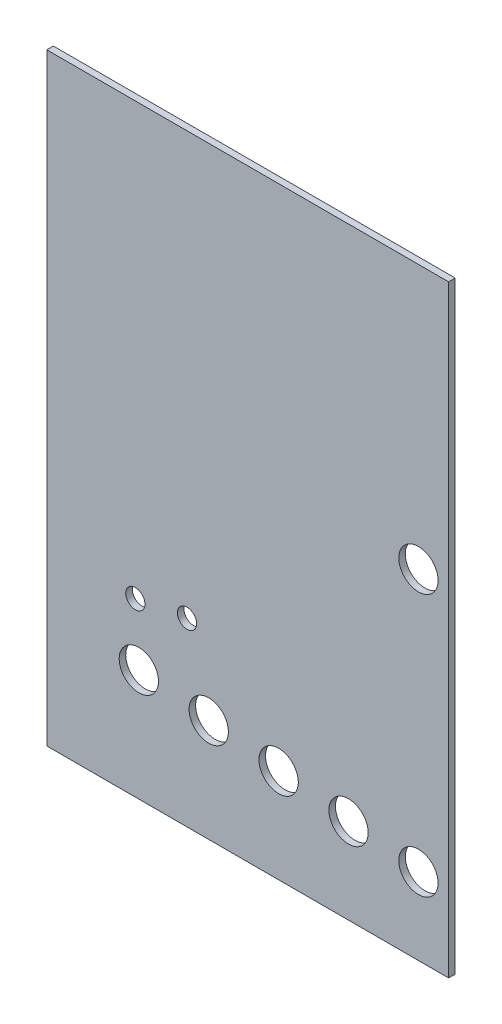
SolidWorks part; units mm, degrees
material "Polypropylene"
ref_plane "Front Plane" through (0, 0, 0) normal (0, 0, 1) x (1, 0, 0)
ref_plane "Top Plane" through (0, 0, 0) normal (0, 1, 0) x (1, 0, 0)
ref_plane "Right Plane" through (0, 0, 0) normal (1, 0, 0) x (0, 0, -1)
sketch "Sketch1" plane through (0, 0, 0) normal (0, 0, 1) x (1, 0, 0)
  line L0 (64.3744, -313.2564) -> (64.3744, -356.9444) construction
  line L1 (0, 0) -> (292.1, 0)
  line L2 (0, 0) -> (0, -438.15)
  line L3 (0, -438.15) -> (292.1, -438.15)
  line L4 (292.1, 0) -> (292.1, -438.15)
  line L5 (64.3744, -313.2564) -> (101.9257, -306.8134) construction
  line L6 (64.3744, -313.2564) -> (101.9257, -313.2564) construction
  line L7 (101.9257, -313.2564) -> (101.9257, -306.8134) construction
  line L8 (64.3744, -356.9444) -> (66.9144, -356.9444) construction
  line L9 (66.9144, -356.9444) -> (117.7144, -356.9444) construction
  line L10 (117.7144, -356.9444) -> (117.7144, -363.2944) construction
  line L11 (117.7144, -363.2944) -> (168.5144, -363.2944) construction
  line L12 (168.5144, -363.2944) -> (168.5144, -369.6444) construction
  line L13 (168.5144, -369.6444) -> (219.3144, -369.6444) construction
  line L14 (219.3144, -369.6444) -> (219.3144, -375.9944) construction
  line L15 (219.3144, -375.9944) -> (270.1144, -375.9944) construction
  line L16 (270.1144, -375.9944) -> (270.1144, -382.3444) construction
  circle A0 centre (101.9257, -306.8134) radius 7
  circle A1 centre (64.3744, -313.2564) radius 7
  circle A2 centre (66.9144, -356.9444) radius 14.2875
  circle A3 centre (117.7144, -363.2944) radius 14.2875
  circle A4 centre (168.5144, -369.6444) radius 14.2875
  circle A5 centre (219.3144, -375.9944) radius 14.2875
  circle A6 centre (270.1144, -382.3444) radius 14.2875
  dimension "D3" = 14
  dimension "D6" = 43.688
  dimension "D8" = 28.575
  dimension "D9" = 28.575
  dimension "D10" = 28.575
  dimension "D17" = 28.575
  dimension "D19" = 28.575
  dimension "D1" = 438.15
  dimension "D2" = 292.1
  dimension "D4" = 38.1
  dimension "D5" = 9.736
  dimension "D7" = 2.54
  dimension "D11" = 50.8
  dimension "D12" = 50.8
  dimension "D13" = 6.35
  dimension "D14" = 50.8
  dimension "D15" = 6.35
  dimension "D16" = 6.35
  dimension "D18" = 50.8
extrude "Boss-Extrude1" add sketch "Sketch1" along normal blind 4.7625
sketch "Sketch2" plane through (0, 0, 4.7625) normal (0, 0, 1) x (1, 0, 0)
  line L0 (270.1144, -382.3444) -> (270.1144, -191.8444) construction
  circle A2 centre (270.1144, -191.8444) radius 14.2875
  dimension "D2" = 28.575
  dimension "D1" = 190.5
extrude "Cut-Extrude3" cut sketch "Sketch2" against normal blind 10.668
